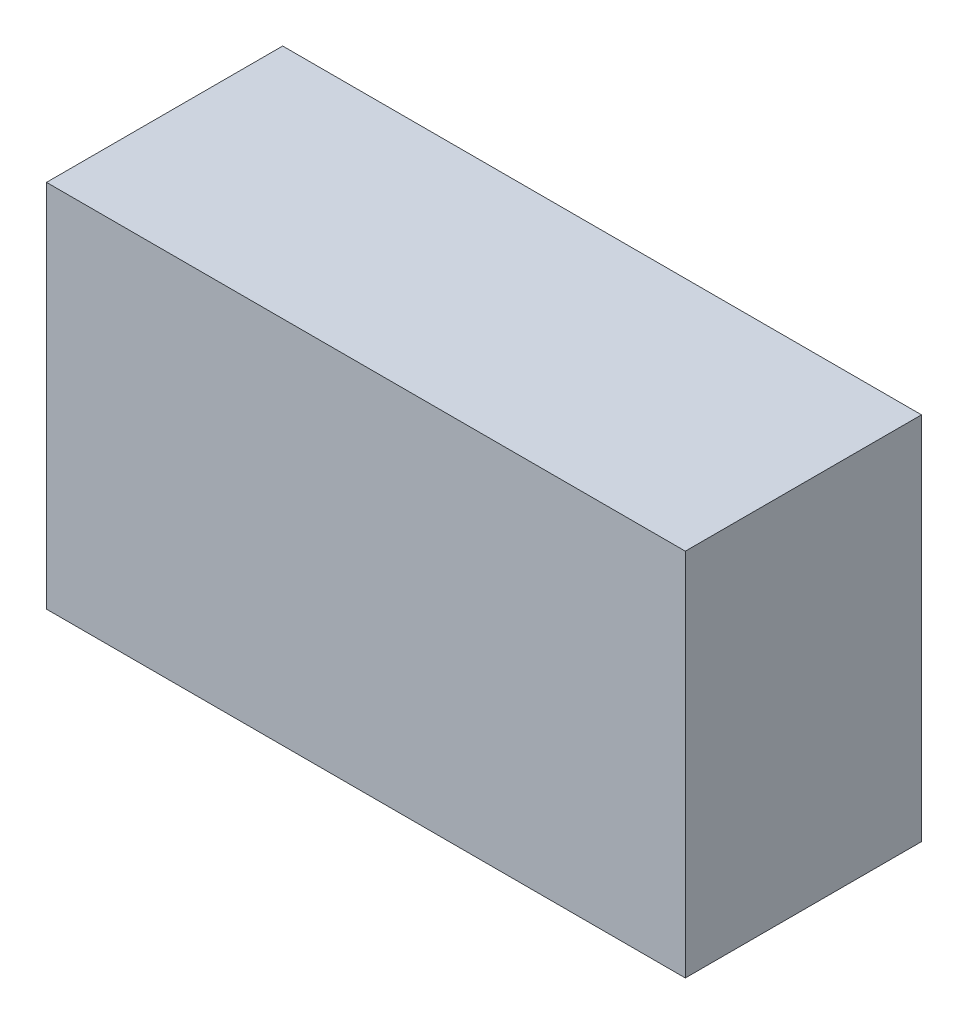
SolidWorks part; units mm, degrees
ref_plane "Front Plane" through (0, 0, 0) normal (0, 0, 1) x (1, 0, 0)
ref_plane "Top Plane" through (0, 0, 0) normal (0, 1, 0) x (1, 0, 0)
ref_plane "Right Plane" through (0, 0, 0) normal (1, 0, 0) x (0, 0, -1)
sketch "Sketch1" plane through (0, 0, 0) normal (0, 0, 1) x (1, 0, 0)
  line L0 (25.5, 31.8941) -> (25.5, 64.9663) construction
  line L1 (24.5, 38.1127) -> (-24.5, 38.1127)
  line L2 (25.5, 38.1127) -> (25.5, 66.4663) construction
  line L3 (24.5, 66.4663) -> (-24.5, 66.4663)
  line L4 (-25.5, 38.1127) -> (-25.5, 66.4663) construction
  line L5 (-25.5, 31.8941) -> (-25.5, 64.9663) construction
  line L6 (-39.45, 66.9663) -> (39.45, 66.9663) construction
  line L7 (24.5, 66.4663) -> (24.5, 38.1127)
  line L8 (-24.5, 66.4663) -> (-24.5, 38.1127)
  dimension "D1" = 0.5
  dimension "D2" = 0.5
  dimension "D3" = 49
  dimension "D4" = 28.3536
  dimension "D5" = 1
  dimension "D6" = 1
extrude "Boss-Extrude1" add sketch "Sketch1" along normal up to surface (18.114 mm away)
